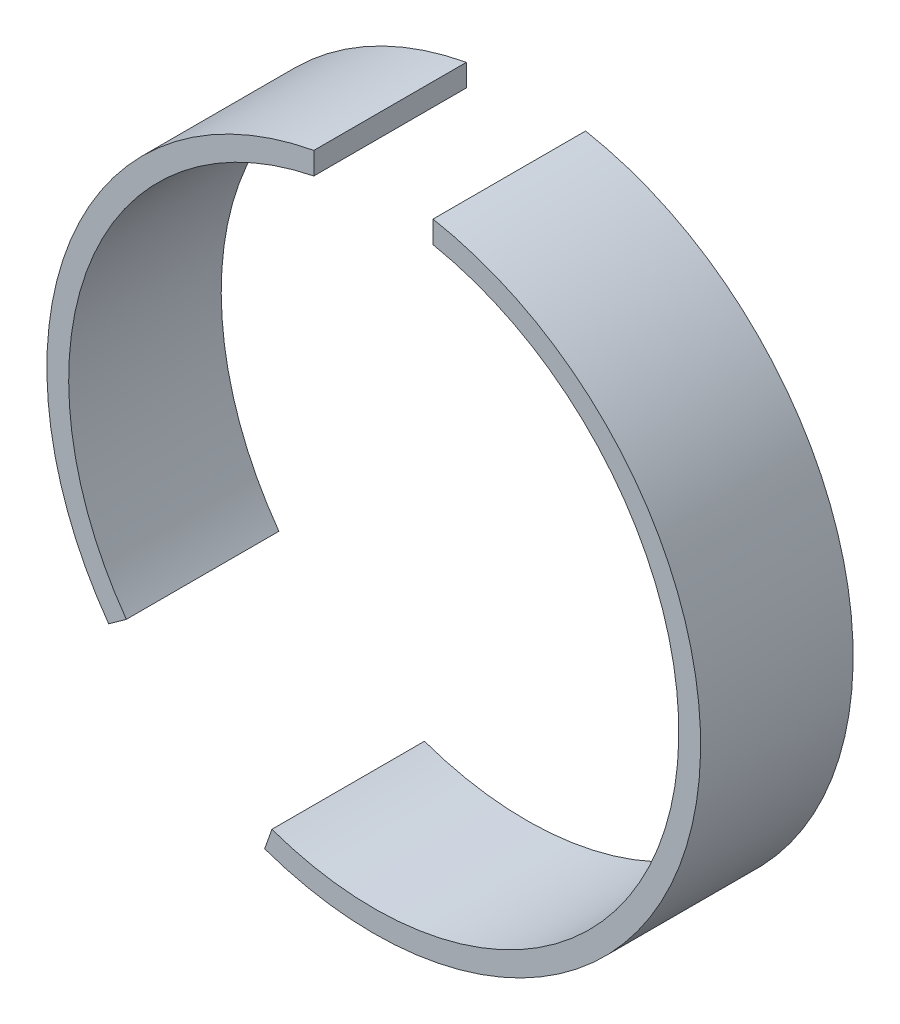
SolidWorks part; units mm, degrees
ref_plane "Front Plane" through (0, 0, 0) normal (0, 0, 1) x (1, 0, 0)
ref_plane "Top Plane" through (0, 0, 0) normal (0, 1, 0) x (1, 0, 0)
ref_plane "Right Plane" through (0, 0, 0) normal (1, 0, 0) x (0, 0, -1)
sketch "Sketch2" plane through (0, 0, 0) normal (0, 0, 1) x (1, 0, 0)
  line L0 (-9.3464, -26.394) -> (-10.014, -28.2793)
  line L1 (5.44, 27.4665) -> (5.44, 29.5027)
  line L7 (-24.3262, -17.5566) -> (-22.7045, -16.3862)
  line L8 (-5.5, 29.4915) -> (-5.5, 27.4545)
  arc A2 (-9.3464, -26.394) -> (5.44, 27.4665) centre (0, 0) ccw
  arc A5 (-5.5, 27.4545) -> (-22.7045, -16.3862) centre (0, 0) ccw
  arc A6 (-10.014, -28.2793) -> (5.44, 29.5027) centre (0, 0) ccw
  arc A7 (-5.5, 29.4915) -> (-24.3262, -17.5566) centre (0, 0) ccw
extrude "Boss-Extrude2" add sketch "Sketch2" along normal blind 14
